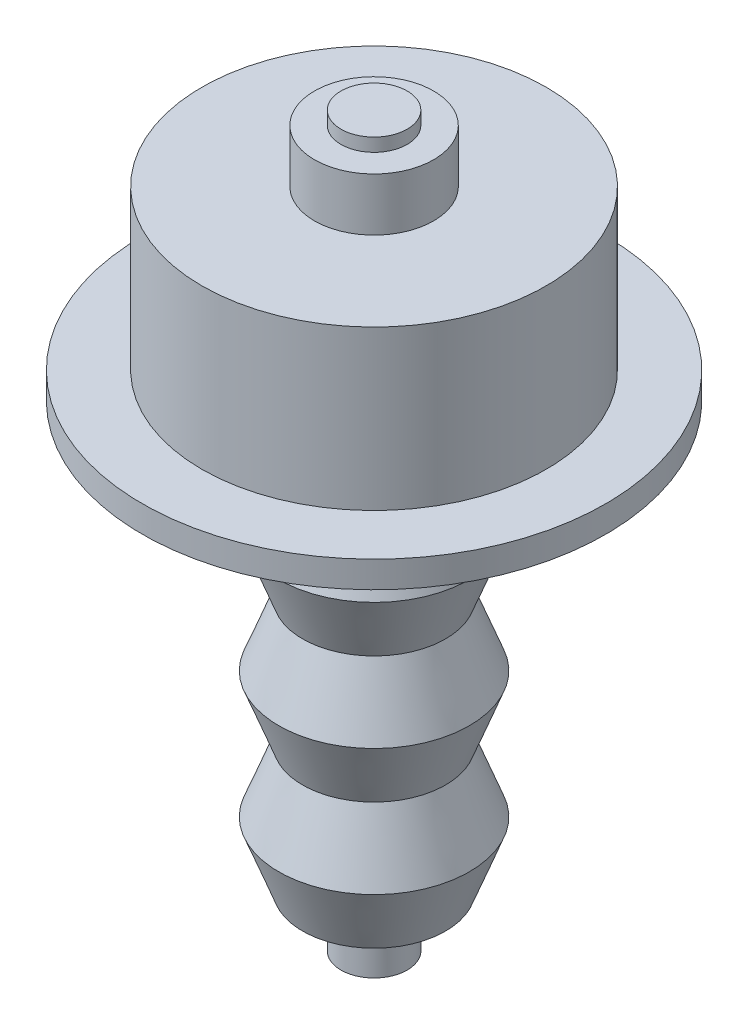
SolidWorks part; units mm, degrees
ref_plane "Front Plane" through (0, 0, 0) normal (0, 0, 1) x (1, 0, 0)
ref_plane "Top Plane" through (0, 0, 0) normal (0, 1, 0) x (1, 0, 0)
ref_plane "Right Plane" through (0, 0, 0) normal (1, 0, 0) x (0, 0, -1)
sketch "SK_P01_Spring" plane through (0, 0, 0) normal (0, 0, 1) x (1, 0, 0)
  line L0 (0, 4) -> (5.4, 4)
  line L1 (5.4, 4) -> (7.2, 8.778)
  line L2 (7.2, 8.778) -> (5.4, 13.556)
  line L3 (5.4, 13.556) -> (7.2, 18.333)
  line L4 (7.2, 18.333) -> (5.4, 23.111)
  line L5 (5.4, 23.111) -> (7.2, 27.889)
  line L6 (7.2, 27.889) -> (5.4, 32.667)
  line L7 (5.4, 32.667) -> (7.2, 37.444)
  line L8 (7.2, 37.444) -> (5.4, 42.222)
  line L9 (5.4, 42.222) -> (7.2, 47)
  line L10 (7.2, 47) -> (0, 47)
  line L11 (0, 47) -> (0, 4)
  line L12 (0, -1) -> (0, 52) construction
revolve "P01_Spring" add sketch "SK_P01_Spring" angle 360 about L12
sketch "SK_P02_Guideboltdroopstop" plane through (0, 0, 0) normal (0, 1, 0) x (1, 0, 0)
  circle A0 centre (0, 0) radius 2.5
extrude "P02_Guideboltdroopstop" add sketch "SK_P02_Guideboltdroopstop" along normal blind 55
sketch "SK_P03_Springcup" plane through (0, 0, 0) normal (0, 0, 1) x (1, 0, 0)
  line L0 (9.5, 36) -> (17.5, 36)
  line L1 (17.5, 36) -> (17.5, 38)
  line L2 (17.5, 38) -> (13, 38)
  line L3 (13, 38) -> (13, 50)
  line L4 (13, 50) -> (0, 50)
  line L5 (0, 50) -> (0, 47)
  line L6 (0, 47) -> (9.5, 47)
  line L7 (9.5, 47) -> (9.5, 36)
  line L8 (0, 31) -> (0, 55) construction
revolve "P03_Springcup" add sketch "SK_P03_Springcup" angle 360 about L8
sketch "SK_P04_Stopnut" plane through (0, 0, 0) normal (0, 1, 0) x (1, 0, 0)
  circle A0 centre (0, 0) radius 4.5
extrude "P04_Stopnut" add sketch "SK_P04_Stopnut" along normal blind 4 from offset 50
